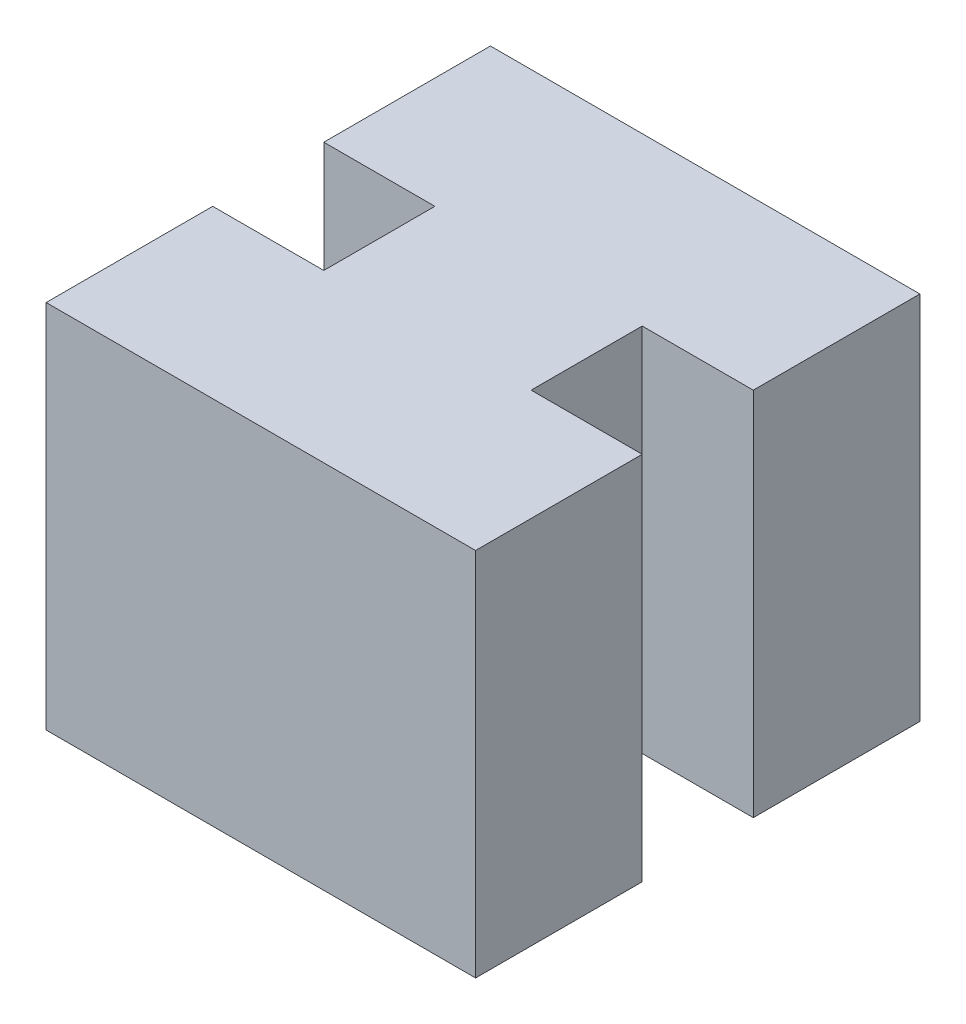
SolidWorks part; units mm, degrees
material "ABS"
ref_plane "Front" through (0, 0, 0) normal (0, 0, 1) x (1, 0, 0)
ref_plane "Top" through (0, 0, 0) normal (0, 1, 0) x (1, 0, 0)
ref_plane "Right" through (0, 0, 0) normal (1, 0, 0) x (0, 0, -1)
sketch "Sketch1" plane through (0, 0, 0) normal (0, 1, 0) x (1, 0, 0)
  line L1 (-2.9, 3) -> (2.9, 3)
  line L2 (-2.9, 3) -> (-2.9, -3)
  line L3 (-2.9, -3) -> (2.9, -3)
  line L4 (2.9, 3) -> (2.9, -3)
  line L5 (-2.9, 3) -> (2.9, -3) construction
  line L6 (-2.9, -3) -> (2.9, 3) construction
  line L7 (-2.9, 0.75) -> (-1.4, 0.75)
  line L8 (-2.9, 0.75) -> (-2.9, -0.75)
  line L9 (-2.9, -0.75) -> (-1.4, -0.75)
  line L10 (-1.4, 0.75) -> (-1.4, -0.75)
  line L11 (-2.9, 0.75) -> (-1.4, -0.75) construction
  line L12 (-2.9, -0.75) -> (-1.4, 0.75) construction
  line L13 (1.4, 0.75) -> (2.9, 0.75)
  line L14 (1.4, 0.75) -> (1.4, -0.75)
  line L15 (1.4, -0.75) -> (2.9, -0.75)
  line L16 (2.9, 0.75) -> (2.9, -0.75)
  line L17 (1.4, 0.75) -> (2.9, -0.75) construction
  line L18 (1.4, -0.75) -> (2.9, 0.75) construction
  point P0 (0, 0)
  point P5 (2.15, 0)
  point P6 (-2.15, 0)
  point P16 (0, 0)
  point P17 (-1.9221, -0.4889)
  dimension "D1" = 5.8
  dimension "D2" = 6
  dimension "D3" = 1.5
extrude "Boss-Extrude1" add sketch "Sketch1" along normal mid plane 5 contours L15 L14 L13 L4 L1 L2 L7 L10 L9 L3
